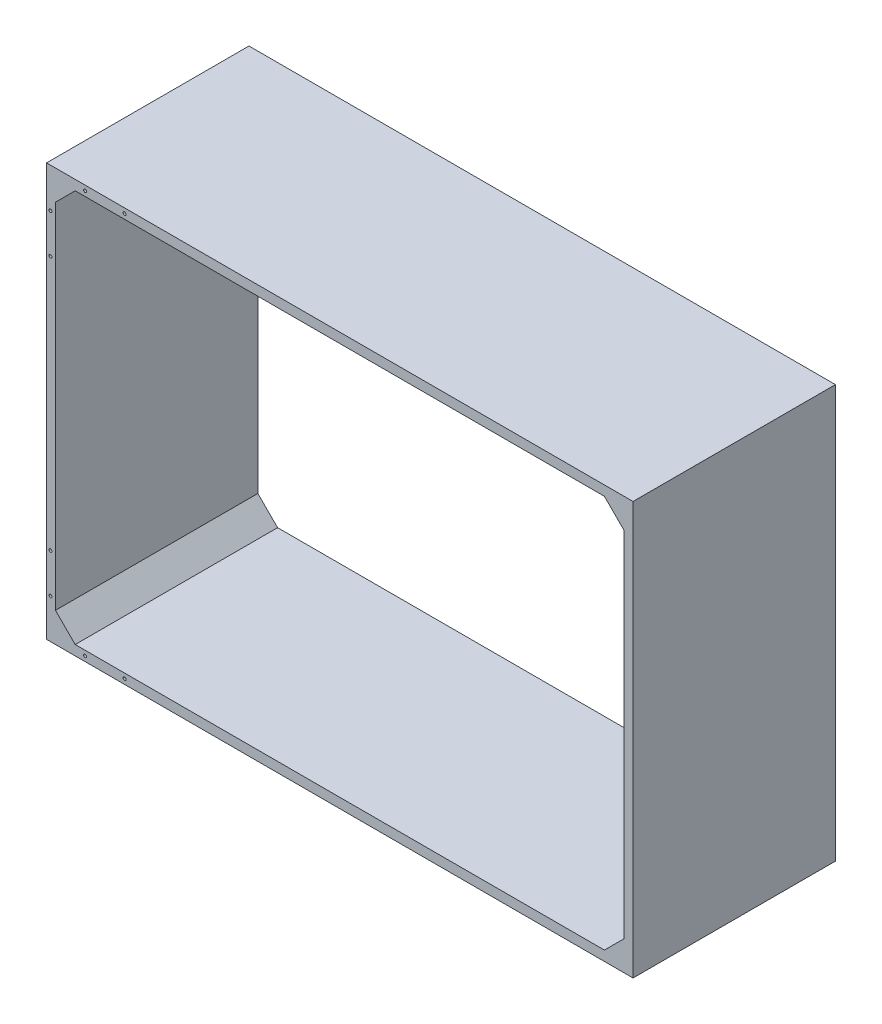
SolidWorks part; units mm, degrees
material "Дуб"
ref_plane "Спереди" through (0, 0, 0) normal (0, 0, 1) x (1, 0, 0)
ref_plane "Сверху" through (0, 0, 0) normal (0, 1, 0) x (1, 0, 0)
ref_plane "Справа" through (0, 0, 0) normal (1, 0, 0) x (0, 0, -1)
ref_plane "Плоскость4" through (0, 0, -205) normal (0, 0, -1) x (-1, 0, 0)
sketch "Эскиз1" plane through (0, 0, -205) normal (0, 0, -1) x (-1, 0, 0)
  line L0 (297, 209) -> (-297, 209)
  line L1 (-297, 209) -> (-297, -209)
  line L2 (-297, -209) -> (297, -209)
  line L3 (297, -209) -> (297, 209)
extrude "Бобышка-Вытянуть1" add sketch "Эскиз1" against normal blind 205
sketch "Эскиз2" plane through (0, 0, 0) normal (0, 0, 1) x (1, 0, 0)
  line L0 (288, 199) -> (-288, 199)
  line L1 (-288, 199) -> (-288, -199)
  line L2 (-288, -199) -> (288, -199)
  line L3 (288, -199) -> (288, 199)
extrude "Вырез-Вытянуть1" cut sketch "Эскиз2" against normal through all
hole_wizard "Диаметр отверстия Ø3.0 (3)1" positions "Эскиз4" profile "Эскиз3" hole size "Ø3.0" standard "Ansi Metric"
sketch "Эскиз4" plane through (0, 0, 0) normal (0, 0, 1) x (1, 0, 0)
  point P0 (-293, -169)
  point P1 (-293, -129)
  point P2 (-258, 204)
  point P3 (-293, 169)
  point P4 (-293, 129)
  point P5 (-218, 204)
  point P6 (-258, -204)
  point P7 (-218, -204)
sketch "Эскиз3" plane through (-293, -169, 0) normal (1, 0, 0) x (0, -1, 0)
  line L0 (0, 0) -> (0, 15)
  line L1 (0, 15) -> (1.5, 14.0987)
  line L2 (1.5, 14.0987) -> (1.5, 0)
  line L5 (1.5, 0) -> (0, 0)
  line L10 (0, 15) -> (-1.5, 14.0987) construction
  line L11 (0, -6.35) -> (0, 107.95) construction
  dimension "Диаметр отверстия" = 3
  dimension "Глубина отверстия" = 14.0987
  dimension "Угол заточки сверла" = 118
chamfer "Фаска1" distance 20 angle 45 4 edges at (288, -199, -102.5) (288, 199, -102.5) (-288, -199, -102.5) (-288, 199, -102.5)
